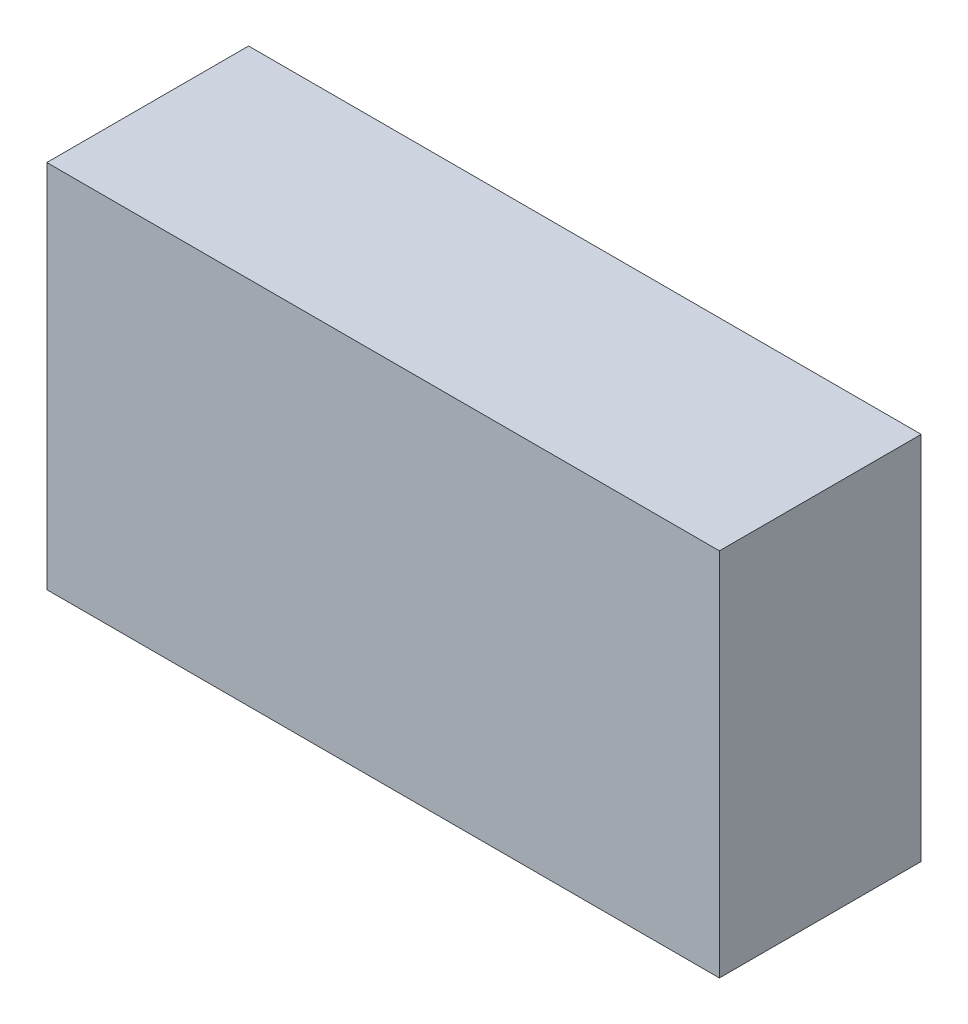
SolidWorks part; units mm, degrees
ref_plane "前视基准面" through (0, 0, 0) normal (0, 0, 1) x (1, 0, 0)
ref_plane "上视基准面" through (0, 0, 0) normal (0, 1, 0) x (1, 0, 0)
ref_plane "右视基准面" through (0, 0, 0) normal (1, 0, 0) x (0, 0, -1)
other "Configuration Table"
sketch "草图1" plane through (0, 0, 0) normal (0, 0, 1) x (1, 0, 0)
  line L1 (-50, -27.5) -> (50, -27.5)
  line L2 (-50, -27.5) -> (-50, 27.5)
  line L3 (-50, 27.5) -> (50, 27.5)
  line L4 (50, -27.5) -> (50, 27.5)
  line L5 (-50, -27.5) -> (50, 27.5) construction
  line L6 (-50, 27.5) -> (50, -27.5) construction
  point P0 (0, 0)
extrude "凸台-拉伸1" add sketch "草图1" along normal blind 30
